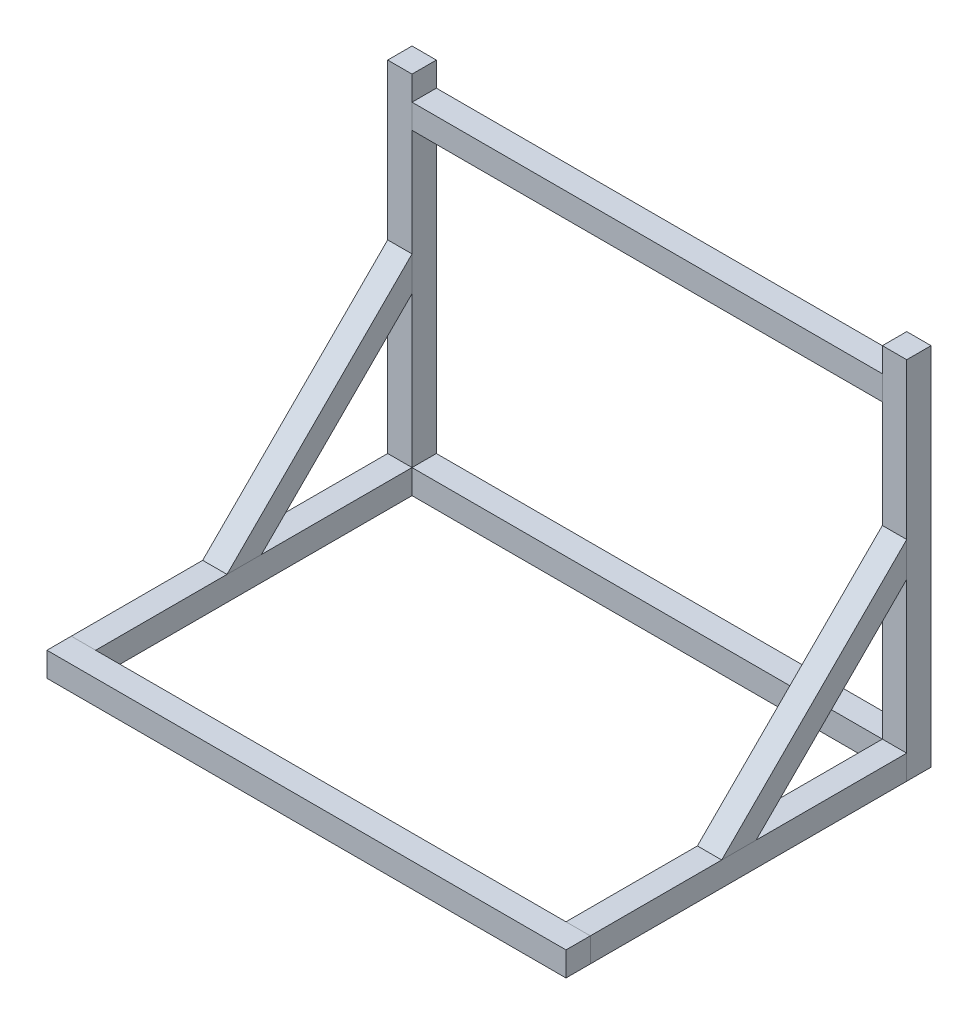
SolidWorks part; units mm, degrees
ref_plane "Front Plane" through (0, 0, 0) normal (0, 0, 1) x (1, 0, 0)
ref_plane "Top Plane" through (0, 0, 0) normal (0, 1, 0) x (1, 0, 0)
ref_plane "Right Plane" through (0, 0, 0) normal (1, 0, 0) x (0, 0, -1)
sketch "ｽｹｯﾁ2" plane through (0, 0, 0) normal (0, 0, 1) x (1, 0, 0)
  line L1 (-184.32, 3.6937) -> (-144.32, 3.6937)
  line L2 (-184.32, 3.6937) -> (-184.32, -36.3063)
  line L3 (-184.32, -36.3063) -> (-144.32, -36.3063)
  line L4 (-144.32, 3.6937) -> (-144.32, -36.3063)
  line L5 (628.68, 3.6937) -> (668.68, 3.6937)
  line L6 (628.68, 3.6937) -> (628.68, -36.3063)
  line L7 (628.68, -36.3063) -> (668.68, -36.3063)
  line L8 (668.68, 3.6937) -> (668.68, -36.3063)
  dimension "D1" = 40
  dimension "D2" = 40
  dimension "D3" = 40
  dimension "D4" = 40
  dimension "D5" = 773
extrude "ﾎﾞｽ - 押し出し1" add sketch "ｽｹｯﾁ2" along normal blind 520
sketch "ｽｹｯﾁ8" plane through (0, -36.3063, 0) normal (0, -1, 0) x (1, 0, 0)
  line L9 (-184.32, 0) -> (-144.32, 0)
  line L10 (-184.32, 0) -> (-184.32, -40)
  line L11 (-184.32, -40) -> (-144.32, -40)
  line L12 (-144.32, 0) -> (-144.32, -40)
  line L13 (628.68, 0) -> (668.68, 0)
  line L14 (628.68, 0) -> (628.68, -40)
  line L15 (628.68, -40) -> (668.68, -40)
  line L16 (668.68, 0) -> (668.68, -40)
  dimension "D1" = 40
  dimension "D2" = 40
  dimension "D3" = 40
  dimension "D4" = 40
extrude "ﾎﾞｽ - 押し出し4" add sketch "ｽｹｯﾁ8" against normal blind 600 separate body
sketch "ｽｹｯﾁ9" plane through (628.68, 0, 0) normal (-1, 0, 0) x (0, 0, 1)
  line L12 (0, 3.6937) -> (-40, 3.6937)
  line L13 (0, 3.6937) -> (0, -36.3063)
  line L14 (0, -36.3063) -> (-40, -36.3063)
  line L15 (-40, 3.6937) -> (-40, -36.3063)
extrude "ﾎﾞｽ - 押し出し6" add sketch "ｽｹｯﾁ9" along normal blind 773 separate body
sketch "ｽｹｯﾁ13" plane through (668.68, 0, 0) normal (1, 0, 0) x (0, 0, -1)
  line L9 (-304.0559, 3.6937) -> (0, 307.7496)
  line L10 (-520, 3.6937) -> (0, 3.6937) construction
  line L11 (0, 563.6937) -> (0, -36.3063) construction
  line L12 (0, 307.7496) -> (0, 251.1811)
  line L13 (0, 251.1811) -> (-247.4874, 3.6937)
  line L14 (-247.4874, 3.6937) -> (-304.0559, 3.6937)
  dimension "D1" = 430
  dimension "D2" = 350
  dimension "D3" = 45
  dimension "D4" = 135
extrude "ﾎﾞｽ - 押し出し7" add sketch "ｽｹｯﾁ13" against normal blind 40
sketch "ｽｹｯﾁ14" plane through (-184.32, 0, 0) normal (-1, 0, 0) x (0, 0, 1)
  line L6 (0, 307.7496) -> (304.0559, 3.6937)
  line L7 (304.0559, 3.6937) -> (247.4874, 3.6937)
  line L8 (247.4874, 3.6937) -> (0, 251.1811)
  line L9 (0, 251.1811) -> (0, 307.7496)
extrude "ﾎﾞｽ - 押し出し8" add sketch "ｽｹｯﾁ14" against normal blind 40
sketch "ｽｹｯﾁ16" plane through (-184.32, 0, 0) normal (-1, 0, 0) x (0, 0, 1)
  line L1 (520, 3.6937) -> (560, 3.6937)
  line L2 (520, 3.6937) -> (520, -36.3063)
  line L3 (520, -36.3063) -> (560, -36.3063)
  line L4 (560, 3.6937) -> (560, -36.3063)
  dimension "D1" = 40
  dimension "D2" = 40
extrude "ﾎﾞｽ - 押し出し9" add sketch "ｽｹｯﾁ16" against normal blind 853 separate body
sketch "ｽｹｯﾁ17" plane through (-144.32, 0, 0) normal (1, 0, 0) x (0, 0, -1)
  line L0 (0, 563.6937) -> (0, -36.3063) construction
  line L1 (0, 523.6937) -> (40, 523.6937)
  line L2 (0, 523.6937) -> (0, 483.6937)
  line L3 (0, 483.6937) -> (40, 483.6937)
  line L4 (40, 523.6937) -> (40, 483.6937)
  line L5 (40, 563.6937) -> (40, -36.3063) construction
  line L6 (40, 563.6937) -> (0, 563.6937) construction
  dimension "D1" = 40
  dimension "D2" = 40
extrude "ﾎﾞｽ - 押し出し10" add sketch "ｽｹｯﾁ17" along normal blind 773 separate body
